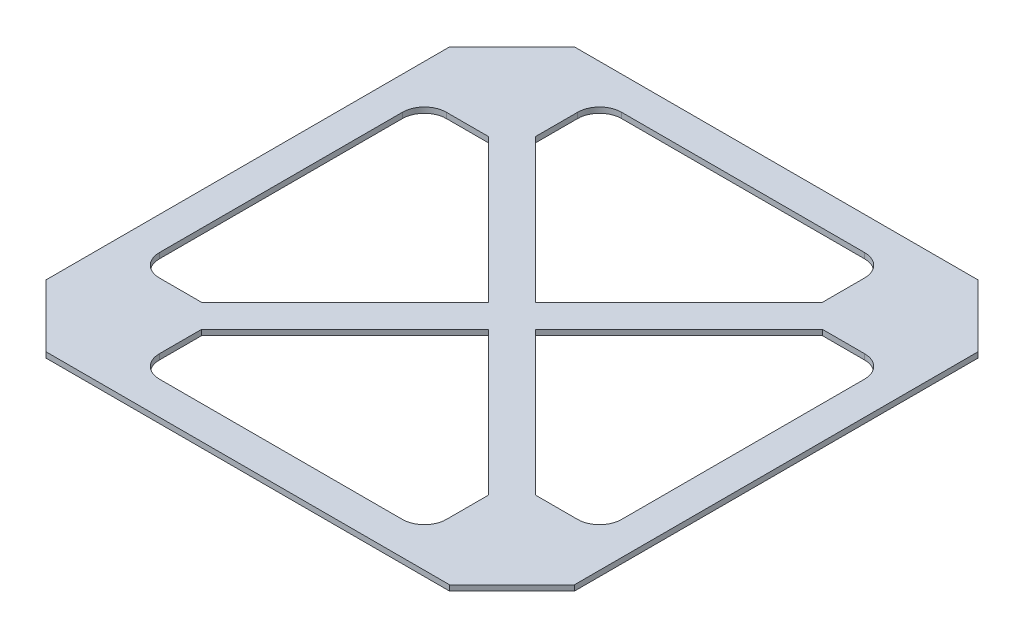
SolidWorks part; units mm, degrees
ref_plane "Front Plane" through (0, 0, 0) normal (0, 0, 1) x (1, 0, 0)
ref_plane "Top Plane" through (0, 0, 0) normal (0, 1, 0) x (1, 0, 0)
ref_plane "Right Plane" through (0, 0, 0) normal (1, 0, 0) x (0, 0, -1)
sketch "Sketch2" plane through (0, 0, 0) normal (0, 1, 0) x (1, 0, 0)
  line L0 (-152.4, 116.479) -> (-116.479, 152.4)
  line L1 (-116.479, 152.4) -> (116.479, 152.4)
  line L2 (-152.4, 116.479) -> (-152.4, -116.479)
  line L3 (-82.803, 96.2734) -> (0, 13.4704)
  line L4 (-116.479, -152.4) -> (116.479, -152.4)
  line L5 (-133.35, 70.103) -> (-133.35, -70.103)
  line L6 (-70.103, 133.35) -> (70.103, 133.35)
  line L7 (-120.65, 82.803) -> (-96.2734, 82.803)
  line L8 (-82.803, 120.65) -> (-82.803, 96.2734)
  line L9 (152.4, 116.479) -> (152.4, -116.479)
  line L10 (82.803, 96.2734) -> (0, 13.4704)
  line L11 (-96.2734, 82.803) -> (-13.4704, 0)
  line L12 (82.803, 120.65) -> (82.803, 96.2734)
  line L13 (96.2734, 82.803) -> (120.65, 82.803)
  line L14 (133.35, 70.103) -> (133.35, -70.103)
  line L15 (-70.103, -133.35) -> (70.103, -133.35)
  line L16 (96.2734, 82.803) -> (13.4704, 0)
  line L17 (-13.4704, 0) -> (-96.2734, -82.803)
  line L18 (0, -13.4704) -> (-82.803, -96.2734)
  line L19 (13.4704, 0) -> (96.2734, -82.803)
  line L20 (0, -13.4704) -> (82.803, -96.2734)
  line L21 (96.2734, -82.803) -> (120.65, -82.803)
  line L22 (82.803, -96.2734) -> (82.803, -120.65)
  line L23 (-82.803, -96.2734) -> (-82.803, -120.65)
  line L24 (-120.65, -82.803) -> (-96.2734, -82.803)
  line L33 (152.4, 116.479) -> (116.479, 152.4)
  line L36 (152.4, -116.479) -> (116.479, -152.4)
  line L57 (-152.4, -116.479) -> (-116.479, -152.4)
  arc A0 (-133.35, 70.103) -> (-120.65, 82.803) centre (-120.65, 70.103) cw
  arc A1 (-70.103, 133.35) -> (-82.803, 120.65) centre (-70.103, 120.65) ccw
  arc A2 (82.803, 120.65) -> (70.103, 133.35) centre (70.103, 120.65) ccw
  arc A3 (133.35, 70.103) -> (120.65, 82.803) centre (120.65, 70.103) ccw
  arc A4 (120.65, -82.803) -> (133.35, -70.103) centre (120.65, -70.103) ccw
  arc A5 (70.103, -133.35) -> (82.803, -120.65) centre (70.103, -120.65) ccw
  arc A6 (-82.803, -120.65) -> (-70.103, -133.35) centre (-70.103, -120.65) ccw
  arc A7 (-133.35, -70.103) -> (-120.65, -82.803) centre (-120.65, -70.103) ccw
  dimension "D3" = 50.8
  dimension "D5" = 19.05
extrude "Boss-Extrude1" add sketch "Sketch2" along normal blind 3.175
